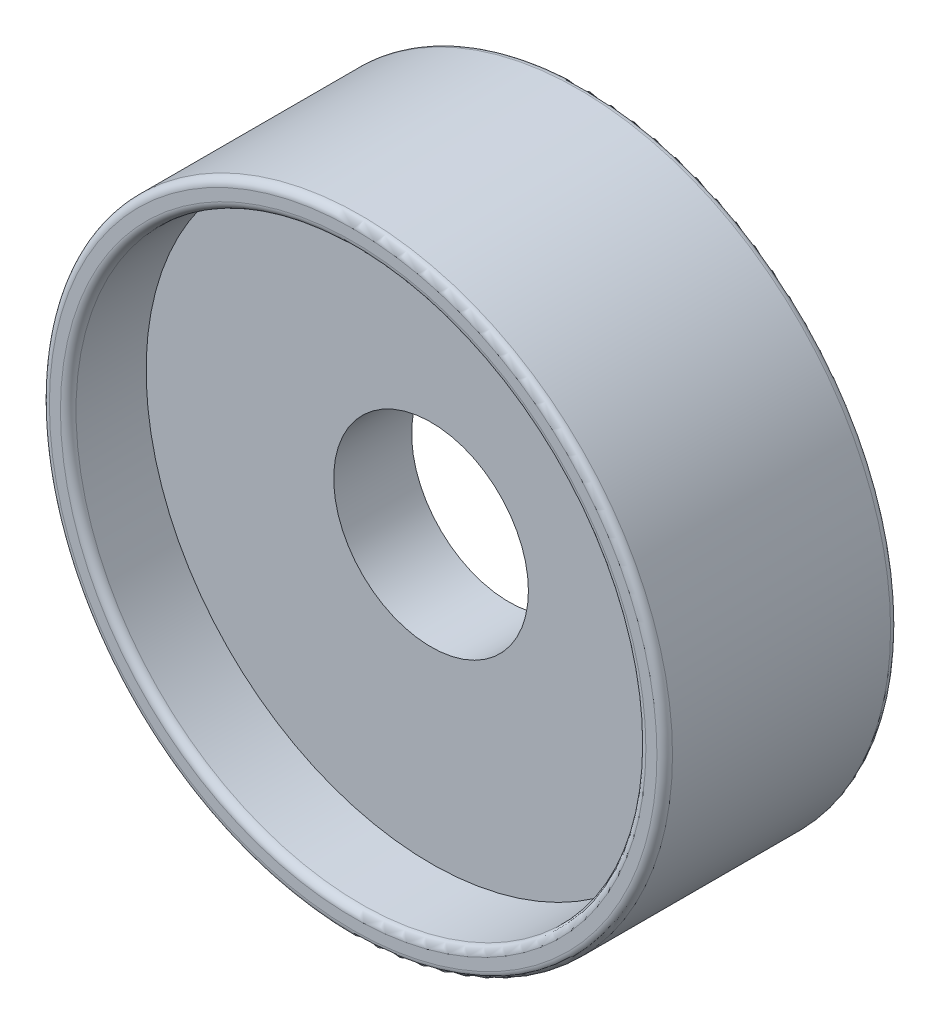
SolidWorks part; units mm, degrees
material "ABS"
ref_plane "Front Plane" through (0, 0, 0) normal (0, 0, 1) x (1, 0, 0)
ref_plane "Top Plane" through (0, 0, 0) normal (0, 1, 0) x (1, 0, 0)
ref_plane "Right Plane" through (0, 0, 0) normal (1, 0, 0) x (0, 0, -1)
sketch "Sketch1" plane through (0, 0, 0) normal (0, 0, 1) x (1, 0, 0)
  circle A0 centre (0, 0) radius 101.6
  circle A1 centre (0, 0) radius 31.75
  dimension "D1" = 203.2
  dimension "D2" = 63.5
extrude "Boss-Extrude1" add sketch "Sketch1" against normal mid plane 76.2
sketch "Sketch2" plane through (0, 0, 38.1) normal (0, 0, 1) x (1, 0, 0)
  circle A0 centre (0, 0) radius 92.9185
extrude "Cut-Extrude1" cut sketch "Sketch2" against normal blind 25.4
mirror "Mirror1" about plane through (0, 0, 0) normal (0, 0, 1) of "Cut-Extrude1"
fillet "Fillet1" radius 2.54 2 edges at (101.6, 0, -38.1) (92.9185, 0, -38.1)
fillet "Fillet2" radius 2.54 2 edges at (101.6, 0, 38.1) (92.9185, 0, 38.1)
